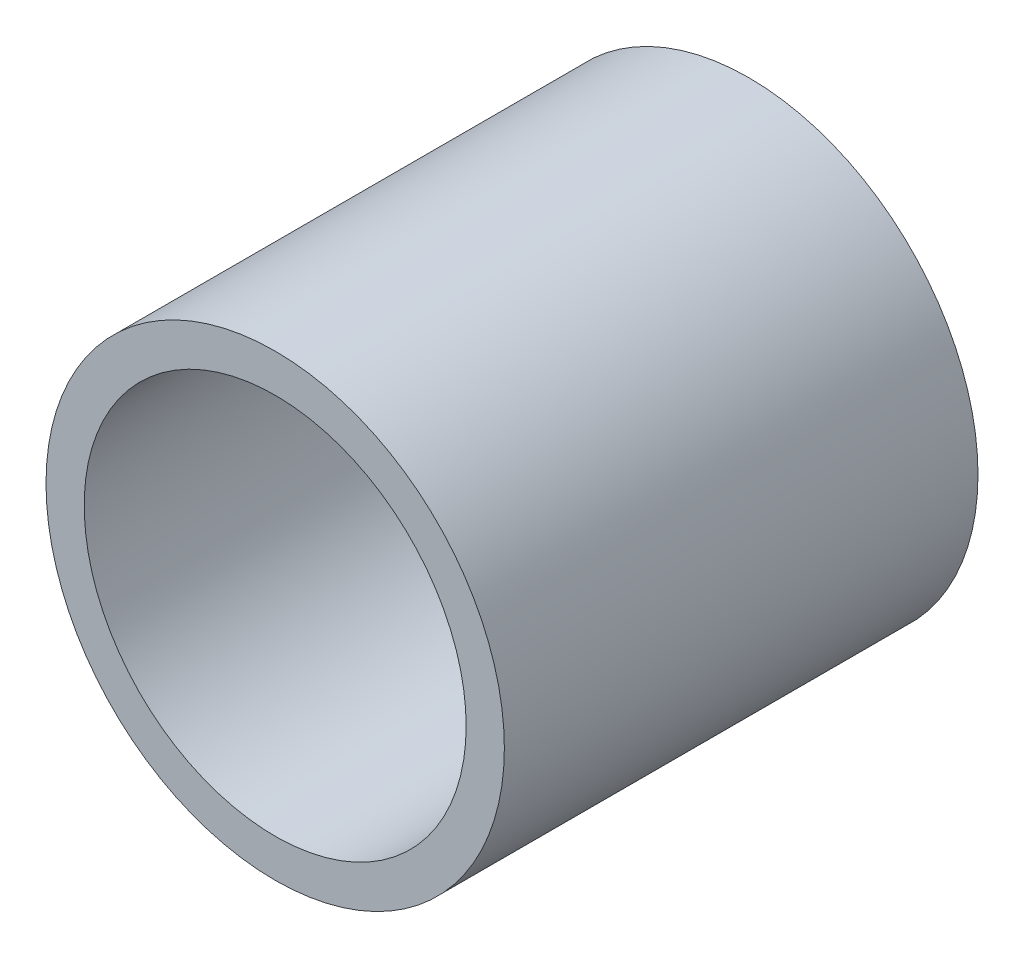
SolidWorks part; units mm, degrees
material "Brass"
ref_plane "Front Plane" through (0, 0, 0) normal (0, 0, 1) x (1, 0, 0)
ref_plane "Top Plane" through (0, 0, 0) normal (0, 1, 0) x (1, 0, 0)
ref_plane "Right Plane" through (0, 0, 0) normal (1, 0, 0) x (0, 0, -1)
sketch "Sketch1" plane through (0, 0, 0) normal (0, 0, 1) x (1, 0, 0)
  circle A0 centre (0, 0) radius 12.5
  circle A1 centre (0, 0) radius 15
  dimension "D1" = 30
  dimension "D2" = 25
extrude "Boss-Extrude1" add sketch "Sketch1" along normal blind 31
